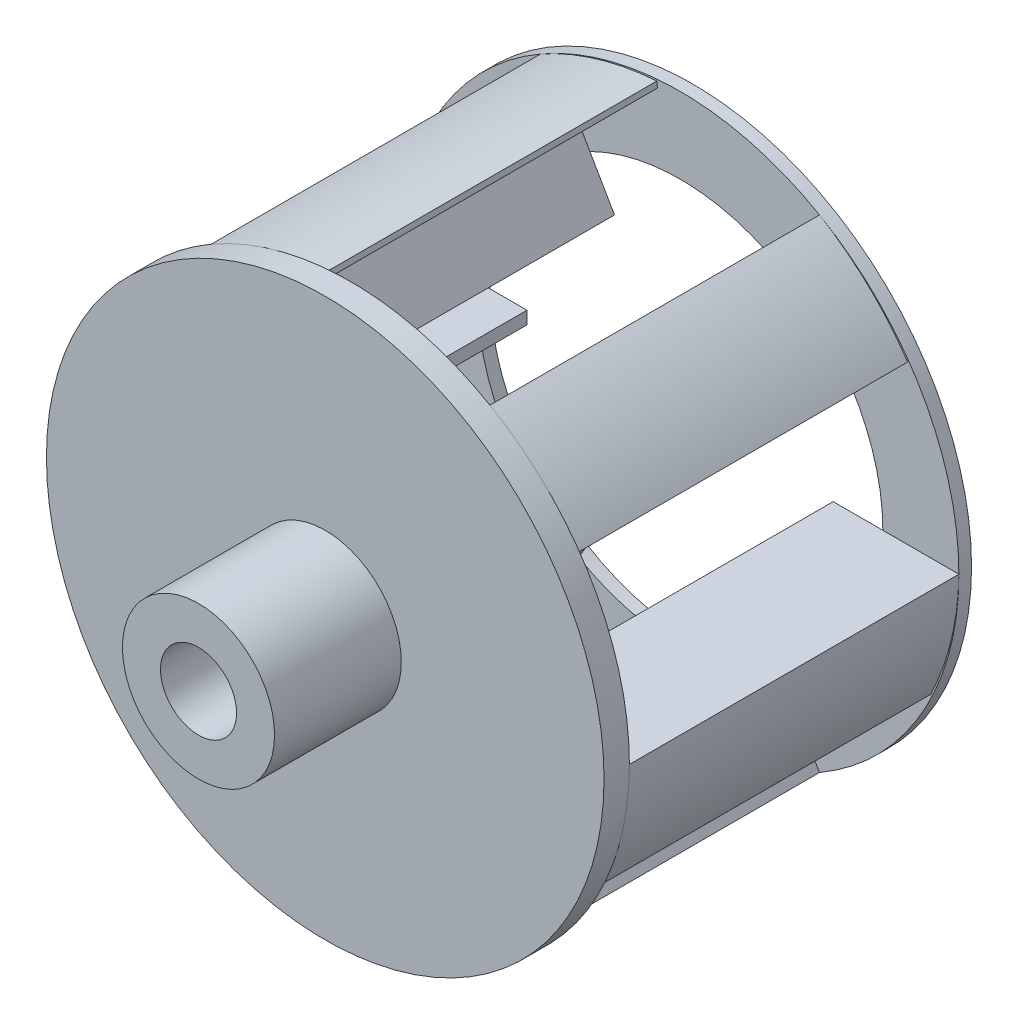
SolidWorks part; units mm, degrees
material "Stainless Steel (ferritic)"
ref_plane "Front Plane" through (0, 0, 0) normal (0, 0, 1) x (1, 0, 0)
ref_plane "Top Plane" through (0, 0, 0) normal (0, 1, 0) x (1, 0, 0)
ref_plane "Right Plane" through (0, 0, 0) normal (1, 0, 0) x (0, 0, -1)
sketch "Sketch1" plane through (0, 0, 0) normal (0, 0, 1) x (1, 0, 0)
  circle A0 centre (0, 0) radius 5.5
  circle A1 centre (0, 0) radius 4
  dimension "D1" = 11
  dimension "D2" = 8
extrude "Boss-Extrude1" add sketch "Sketch1" along normal blind 0.25
ref_plane "Plane1" through (0, 0, 6.75) normal (0, 0, 1) x (1, 0, 0)
sketch "Sketch2" plane through (0, 0, 6.75) normal (0, 0, 1) x (1, 0, 0)
  circle A0 centre (0, 0) radius 5.5
  dimension "D1" = 11
extrude "Boss-Extrude2" add sketch "Sketch2" along normal blind 0.5 separate body
sketch "Sketch3" plane through (0, 0, 7.25) normal (0, 0, 1) x (1, 0, 0)
  circle A0 centre (0, 0) radius 1.5
  dimension "D1" = 3
extrude "Boss-Extrude3" add sketch "Sketch3" along normal blind 2.5
sketch "Sketch4" plane through (0, 0, 9.75) normal (0, 0, 1) x (1, 0, 0)
  circle A0 centre (0, 0) radius 0.75
  dimension "D1" = 1.5
extrude "Cut-Extrude1" cut sketch "Sketch4" against normal blind 5.5
sketch "Sketch5" plane through (0, 0, 0.25) normal (0, 0, 1) x (1, 0, 0)
  line L0 (0, 0) -> (5.5, 0) construction
  line L1 (5.5, 0) -> (3.02, 0)
  line L2 (3.02, 0) -> (3.02, -0.25)
  line L3 (3.02, -0.25) -> (5.3442, -0.25)
  line L4 (0, 0) -> (4.9764, -2.3422) construction
  line L5 (4.8406, -2.2783) -> (4.9459, -2.3279)
  line L6 (5.4907, -0.25) -> (5.4943, -0.25)
  circle A0 centre (0, 0) radius 5.5 construction
  arc A1 (5.5, 0) -> (4.9764, -2.3422) centre (0, 0) cw
  arc A2 (5.5, 0) -> (5.4038, 1.1063) centre (0, 0.0792) cw
  arc A3 (5.3442, -0.25) -> (4.8406, -2.2783) centre (0, 0) cw
  arc A4 (5.35, 0) -> (4.8406, -2.2783) centre (0, 0) cw construction
  circle M4 centre (0, 0) radius 4
  dimension "D1" = 2.48
  dimension "D2" = 0.25
  dimension "D3" = 2.4
  dimension "D4" = 0.15
extrude "Boss-Extrude4" add sketch "Sketch5" along normal up to surface (6.5 mm away) contours L3 A3 L5 A2 L1 M4 | L2 L3 L1 M4
pattern_circular "CirPattern1" count 6 over 360 about axis through (0, 0, 0) along (0, 0, 1) of "Boss-Extrude4"
